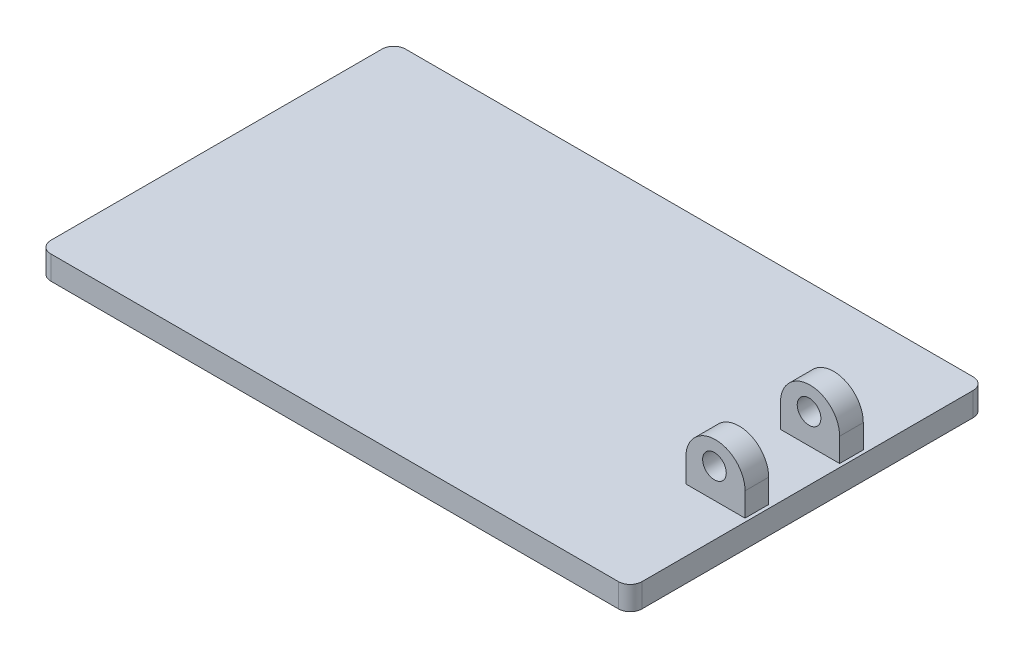
SolidWorks part; units mm, degrees
ref_plane "Front Plane" through (0, 0, 0) normal (0, 0, 1) x (1, 0, 0)
ref_plane "Top Plane" through (0, 0, 0) normal (0, 1, 0) x (1, 0, 0)
ref_plane "Right Plane" through (0, 0, 0) normal (1, 0, 0) x (0, 0, -1)
sketch "Sketch1" plane through (0, 0, 0) normal (0, 1, 0) x (1, 0, 0)
  line L1 (-250, 150) -> (250, 150)
  line L2 (-250, 150) -> (-250, -150)
  line L3 (-250, -150) -> (250, -150)
  line L4 (250, 150) -> (250, -150)
  line L5 (-250, 150) -> (250, -150) construction
  line L6 (-250, -150) -> (250, 150) construction
  point P0 (0, 0)
  dimension "D1" = 300
  dimension "D2" = 500
extrude "Boss-Extrude1" add sketch "Sketch1" along normal blind 20
sketch "Sketch2" plane through (0, 0, 150) normal (0, 0, 1) x (1, 0, 0)
  line L0 (-250, 20) -> (250, 20) construction
  line L2 (197.0915, 40) -> (197.0915, 0)
  line L3 (197.0915, 0) -> (247.0915, 0)
  line L4 (247.0915, 40) -> (247.0915, 0)
  arc A1 (247.0915, 40) -> (197.0915, 40) centre (222.0915, 40) ccw
  point P0 (222.0915, 20)
extrude "Boss-Extrude2" add sketch "Sketch2" along direction (0, 0, 1) on the side against the normal blind 20 from offset 100 offset against normal yes
mirror "Mirror1" about plane through (0, 0, 0) normal (0, 0, 1) of "Boss-Extrude2"
sketch "Sketch3" plane through (0, 0, 50) normal (0, 0, 1) x (1, 0, 0)
  circle A0 centre (221.2201, 45.1211) radius 10
  dimension "D1" = 20
extrude "Cut-Extrude1" cut sketch "Sketch3" against normal blind 286
fillet "Fillet1" radius 10 4 edges at (-250, 10, -150) (250, 10, -150) (250, 10, 150) (-250, 10, 150)
